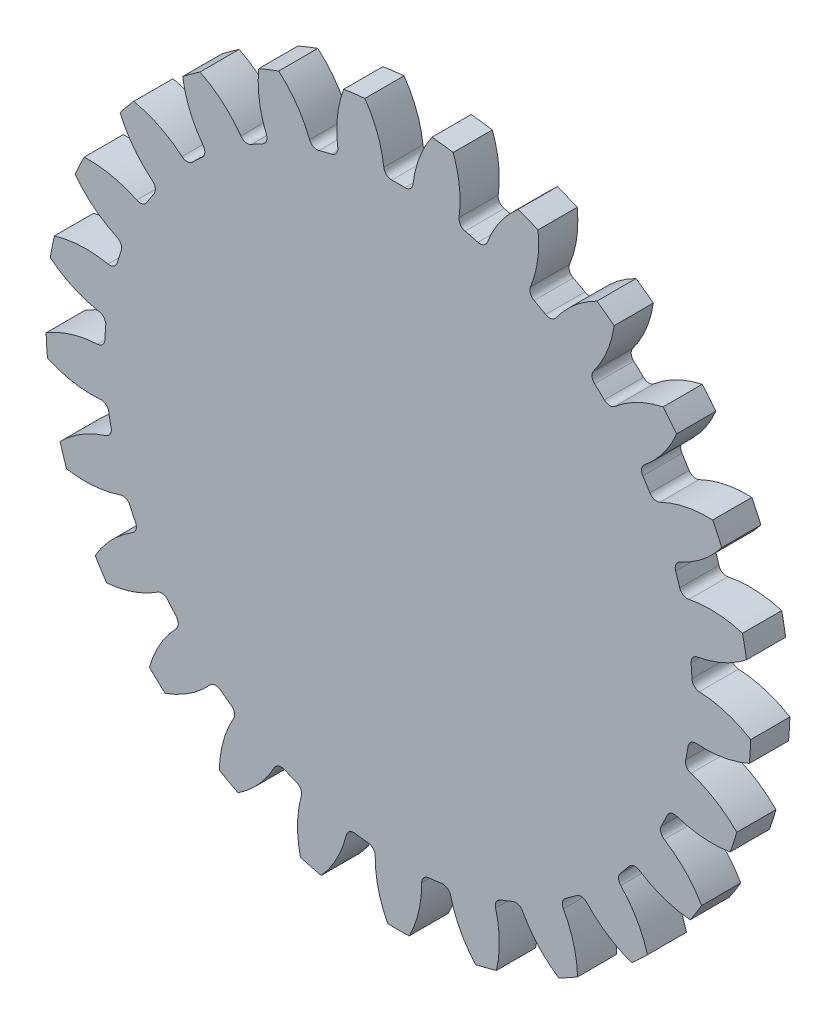
SolidWorks part; units mm, degrees
ref_plane "Front Plane" through (0, 0, 0) normal (0, 0, 1) x (1, 0, 0)
ref_plane "Top Plane" through (0, 0, 0) normal (0, 1, 0) x (1, 0, 0)
ref_plane "Right Plane" through (0, 0, 0) normal (1, 0, 0) x (0, 0, -1)
sketch "Sketch1" plane through (0, 0, 0) normal (0, 0, 1) x (1, 0, 0)
  circle A0 centre (0, 0) radius 635
  circle A1 centre (0, 0) radius 685.8
  circle A2 centre (0, 0) radius 571.5
  dimension "RootDiaCalc" = 1270
  dimension "OutsideDiaCalc" = 1371.6
  dimension "WholeDepthCalc" = 114.3
extrude "Boss-Extrude1" add sketch "Sketch1" along normal blind 76.2 contours A1
sketch "Sketch2" plane through (0, 0, 76.2) normal (0, 0, 1) x (1, 0, 0)
  line L0 (0, 0) -> (0, 685.8) construction
  line L1 (-39.872, 633.747) -> (39.872, 633.747) construction
  line L2 (-27.2294, 570.851) -> (0, 0) construction
  line L3 (0, 524.1996) -> (-58.2801, 684.3228) construction
  line L4 (0, 0) -> (85.9535, 680.3923) construction
  line L5 (39.872, 633.747) -> (118.9871, 623.7524) construction
  circle A0 centre (0, 0) radius 685.8 construction
  arc A1 (-27.2294, 570.851) -> (-65.9134, 683.6298) centre (-240.6465, 560.671) ccw
  arc A2 (27.2294, 570.851) -> (65.9134, 683.6298) centre (240.6465, 560.671) cw
  circle A4 centre (0, 0) radius 571.5 construction
  arc A6 (27.2294, 570.851) -> (-27.2294, 570.851) centre (0, 0) ccw
  arc A7 (65.9134, 683.6298) -> (-65.9134, 683.6298) centre (0, 0) ccw
  circle A8 centre (0, 0) radius 685.8 construction
  circle A9 centre (0, 0) radius 635 construction
  dimension "SafetyOffset" = 1
  dimension "PressureAngleCalc" = 20
  dimension "AngleLineUpCalc" = 7.2
extrude "Cut-Extrude1" cut sketch "Sketch2" against normal up to surface (76.2 mm away) up to face at (685.8, 0, 0)
fillet "Fillet1" radius 15.24 2 edges at (27.2294, 570.851, 38.1) (-27.2294, 570.851, 38.1)
pattern_circular "CirPattern1" count 25 over 360 about axis through (0, 0, 0) along (0, 0, 1) of "Cut-Extrude1", "Fillet1"
equation "\"Module\"= \"Root Diameter\" / \"Number of Teeth\""
equation "\"Number of Teeth\"= 25"
equation "\"RootDiaCalc@Sketch1\" = \"Module\" * \"Number of Teeth\""
equation "\"OutsideDiaCalc@Sketch1\" = \"Module\" *  ( \"Number of Teeth\" + 2 ) "
equation "\"WholeDepthCalc@Sketch1\" = \"Module\" * IIF ( \"Module\" =  > 1.25 , 2.25 , 2.4 ) "
equation "\"AngleLineUpCalc@Sketch2\" = 180 / \"Number of Teeth\""
equation "\"D1@Fillet1\"=\"Module\"*0.3"
equation "\"D1@CirPattern1\"=\"Number of Teeth\""
equation "\"Pressure Angle\"= 20deg"
equation "\"PressureAngleCalc@Sketch2\"=\"Pressure Angle\""
equation "\"Root Diameter\"= 50in"
equation "\"Gear Width\"= 3in"
equation "\"D1@Boss-Extrude1\"=\"Gear Width\""
equation "\"Circular Pitch\"= \"Root Diameter\" * 3.141592 / \"Number of Teeth\""
